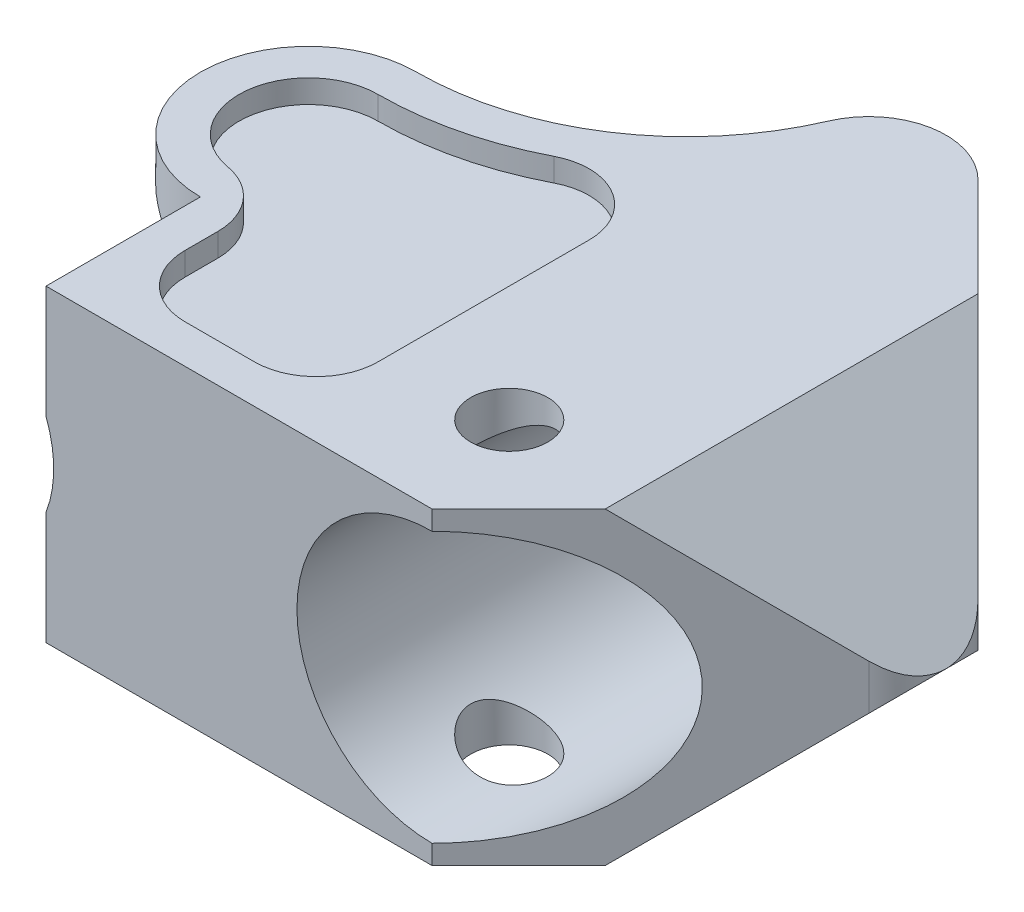
SolidWorks part; units mm, degrees
material "1060 Alloy"
ref_plane "Front Plane" through (0, 0, 0) normal (0, 0, 1) x (1, 0, 0)
ref_plane "Top Plane" through (0, 0, 0) normal (0, 1, 0) x (1, 0, 0)
ref_plane "Right Plane" through (0, 0, 0) normal (1, 0, 0) x (0, 0, -1)
sketch "Sketch1" plane through (0, 0, 0) normal (0, 1, 0) x (1, 0, 0)
  line L0 (0, 0) -> (50, 0)
  line L1 (50, 0) -> (78.2843, 28.2843)
  line L2 (78.2843, 42.4264) -> (48.4126, 72.2981)
  line L3 (0, 0) -> (0, 20)
  line L4 (-80.8464, 34) -> (138.1304, 34) construction
  line L7 (0, 120.0502) -> (0, -87.3472) construction
  arc A1 (48.4126, 72.2981) -> (32.1545, 69.1766) centre (41.3415, 65.227) ccw
  arc A2 (32.1545, 69.1766) -> (0, 48) centre (0, 83) cw
  arc A3 (0, 48) -> (0, 20) centre (0, 34) ccw
  arc A4 (78.2843, 28.2843) -> (78.2843, 42.4264) centre (71.2132, 35.3553) ccw
  point P7 (85.3553, 48)
  point P15 (0, 83)
  point P16 (85.3553, 42.0131)
  point P17 (0, 0)
  point P20 (0, 20)
  point P21 (0, 48)
  point P22 (0, 0)
  point P23 (50, 80.5988)
  point P24 (114.3551, 5.5952)
  point P25 (121.3192, 5.4178)
  point P27 (85.3553, 35.3553)
  point P28 (43.8661, 70.381)
  point P29 (0, 0)
  dimension "D4" = 14
  dimension "D5" = 35
  dimension "D8" = 10
  dimension "D1" = 50
  dimension "D3" = 20
  dimension "D7" = 135
  dimension "D2" = 50
extrude "Boss-Extrude1" add sketch "Sketch1" along normal blind 40
sketch "Sketch2" plane through (0, 40, 0) normal (0, 1, 0) x (1, 0, 0)
  line L4 (30, 13) -> (30, 40.3385)
  line L8 (5, 26.5167) -> (5, 5)
  line L9 (5, 5) -> (47.9289, 5)
  line L10 (47.9289, 5) -> (74.7487, 31.8198)
  line L11 (74.7487, 38.8909) -> (44.8771, 68.7626)
  line L12 (5, 17.2668) -> (5, 13)
  line L13 (13, 5) -> (22, 5)
  arc A4 (13, 5) -> (5, 13) centre (13, 13) cw
  arc A5 (22, 5) -> (30, 13) centre (22, 13) ccw
  arc A6 (30, 40.3385) -> (18.3333, 47.4488) centre (22, 40.3385) ccw
  arc A7 (5, 17.2668) -> (-1.5882, 25.1412) centre (-3, 17.2668) ccw
  arc A8 (74.7487, 31.8198) -> (74.7487, 38.8909) centre (71.2132, 35.3553) ccw
  arc A9 (44.8771, 68.7626) -> (36.748, 67.2018) centre (41.3415, 65.227) ccw
  arc A10 (0, 43) -> (36.748, 67.2018) centre (0, 83) ccw
  arc A11 (0, 43) -> (5, 26.5167) centre (0, 34) ccw
  arc A14 (0, 43) -> (18.3333, 47.4488) centre (0, 83) ccw
  arc A15 (0, 43) -> (-1.5882, 25.1412) centre (0, 34) ccw
  dimension "D3" = 8
  dimension "D2" = 25
  dimension "D1" = 5
extrude "Cut-Extrude1" cut sketch "Sketch2" against normal blind 3
sketch "Sketch3" plane through (0, 0, 0) normal (0, 0, 1) x (1, 0, 0)
  line L0 (-38.3052, 20) -> (67.5, 20) construction
  line L1 (50, -42.1089) -> (50, 75.6561) construction
  line L2 (0, 0) -> (50, 0) construction
  line L3 (-14, 40) -> (-14, 0) construction
  line L5 (-14, 35) -> (-14, 5)
  line L10 (81.2132, 0) -> (81.2132, 40) construction
  line L21 (81.2132, 20) -> (111.7242, 20) construction
  circle A0 centre (50, 20) radius 17.5
  arc A1 (-14, 35) -> (-14, 5) centre (-14, 20) cw
  point P12 (0, 0)
  dimension "D3" = 35
  dimension "D4" = 15
  dimension "D1" = 20
  dimension "D2" = 64
extrude "Cut-Extrude2" cut sketch "Sketch3" against normal through all both and the other way through all
sketch "Sketch4" plane through (0, 40, 0) normal (0, 1, 0) x (1, 0, 0)
  line L0 (0, 20) -> (0, 0) construction
  line L1 (0, 0) -> (50, 0) construction
  circle A0 centre (45, 15) radius 5
  dimension "D3" = 10
  dimension "D1" = 45
  dimension "D2" = 15
sketch "Sketch5" plane through (0, 0, 0) normal (0, 0, 1) x (1, 0, 0)
  line L0 (61.2132, 40) -> (81.2132, 20)
  line L1 (50, 40) -> (78.2843, 40) construction
  line L2 (81.2132, 0) -> (81.2132, 40) construction
  line L3 (81.2132, 20) -> (61.2132, 0)
  line L4 (50, 0) -> (78.2843, 0) construction
  line L5 (78.2843, 0) -> (81.2132, 0) construction
  line L6 (81.2132, 40) -> (78.2843, 40) construction
  line L7 (78.2843, 0) -> (81.2132, 0)
  line L8 (61.2132, 0) -> (78.2843, 0)
  line L9 (81.2132, 0) -> (81.2132, 40)
  line L10 (81.2132, 40) -> (78.2843, 40)
  line L11 (61.2132, 40) -> (78.2843, 40)
  dimension "D1" = 20
extrude "Cut-Extrude3" [suppressed] cut sketch "Sketch5" against normal through all contours L11 L0 L9 L10 | L7 L9 L3 L8
extrude "Cut-Extrude4" cut sketch "Sketch4" against normal through all
sketch "Sketch6" plane through (0, 40, 0) normal (0, 1, 0) x (1, 0, 0)
  line L0 (61.2132, 59.4975) -> (61.2132, 11.2132)
  line L1 (78.2843, 42.4264) -> (48.4126, 72.2981) construction
  line L2 (50, 0) -> (78.2843, 28.2843) construction
  line L3 (61.2132, 11.2132) -> (78.2843, 28.2843)
  line L4 (78.2843, 42.4264) -> (61.2132, 59.4975)
  arc A0 (78.2843, 28.2843) -> (78.2843, 42.4264) centre (71.2132, 35.3553) ccw construction
  arc A1 (78.2843, 28.2843) -> (78.2843, 42.4264) centre (71.2132, 35.3553) ccw
  point P9 (81.2132, 35.3553)
  dimension "D1" = 20
extrude "Cut-Extrude5" [suppressed] cut sketch "Sketch6" against normal through all
sketch "Sketch7" plane through (0, 0, 0) normal (0, 0, 1) x (1, 0, 0)
  line L0 (61.2132, 40) -> (81.2132, 20)
  line L1 (50, 40) -> (78.2843, 40) construction
  line L2 (81.2132, 0) -> (81.2132, 40) construction
  line L3 (81.2132, 20) -> (61.2132, 0)
  line L4 (50, 0) -> (78.2843, 0) construction
  dimension "D1" = 20
extrude "Cut-Extrude6" cut sketch "Sketch7" against normal through all both and the other way through all
equation "\"A\"= 50"
equation "\"B\" = 15"
equation "\"C\"= \"B\" + 20"
equation "\"D1@Sketch1\"=\"A\""
equation "\"D3@Sketch3\"=\"C\""
equation "\"D2@Sketch1\"=\"A\""
equation "\"D4@Sketch3\"=\"B\""
